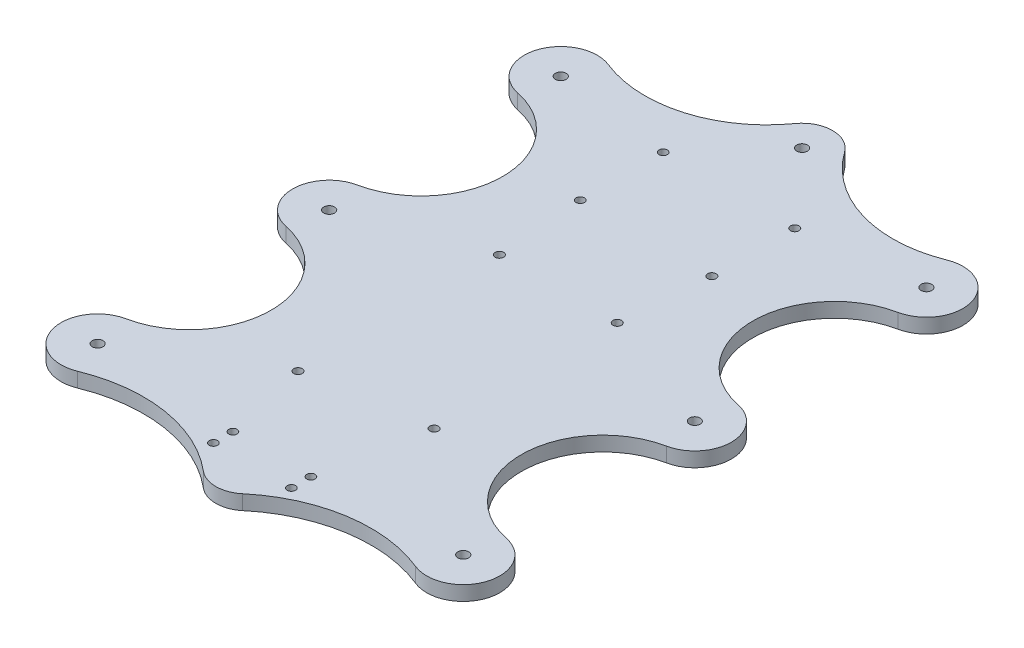
SolidWorks part; units mm, degrees
ref_plane "Front Plane" through (0, 0, 0) normal (0, 0, 1) x (1, 0, 0)
ref_plane "Top Plane" through (0, 0, 0) normal (0, 1, 0) x (1, 0, 0)
ref_plane "Right Plane" through (0, 0, 0) normal (1, 0, 0) x (0, 0, -1)
sketch "Sketch1" plane through (0, 0, 0) normal (0, 1, 0) x (1, 0, 0)
  line L0 (-75, 0) -> (75, 0) construction
  line L1 (-75, -95) -> (-75, -190) construction
  line L3 (0, 0) -> (0, -204) construction
  line L4 (0, 0) -> (0, 24)
  circle A0 centre (-75, 0) radius 15
  circle A1 centre (75, 0) radius 15
  circle A2 centre (-75, -95) radius 15
  circle A3 centre (75, -95) radius 15
  circle A4 centre (-75, -190) radius 15
  circle A5 centre (75, -190) radius 15
  circle A6 centre (-84.798, -142.5) radius 33.5
  circle A10 centre (0, -204) radius 12.5
  circle A11 centre (0, 24) radius 12.5
  circle A12 centre (-46.7001, -259.4559) radius 60
  circle A13 centre (46.7001, -259.4559) radius 60
  circle A14 centre (-50.8455, 60.3453) radius 50
  circle A15 centre (50.8455, 60.3453) radius 50
  circle A16 centre (84.798, -142.5) radius 33.5
  circle A17 centre (-84.798, -47.5) radius 33.5
  circle A18 centre (84.798, -47.5) radius 33.5
  dimension "D3" = 30
  dimension "D4" = 30
  dimension "D10" = 25
  dimension "D12" = 25
  dimension "D13" = 120
  dimension "D14" = 120
  dimension "D15" = 100
  dimension "D16" = 100
  dimension "D6" = 67
  dimension "D7" = 67
  dimension "D8" = 67
  dimension "D17" = 67
  dimension "D1" = 3
  dimension "D2" = 150
  dimension "D5" = 95
  dimension "D9" = 228
  dimension "D11" = 24
extrude "Boss-Extrude1" add sketch "Sketch1" along normal blind 6
sketch "Sketch2" plane through (0, 0, 0) normal (0, -1, 0) x (1, 0, 0)
  circle A0 centre (-75, 190) radius 2.2
  circle A1 centre (-75, 95) radius 2.2
  circle A2 centre (-75, 0) radius 2.2
  circle A3 centre (75, 0) radius 2.2
  circle A4 centre (75, 95) radius 2.2
  circle A5 centre (75, 190) radius 2.2
  dimension "D1" = 4.4
  dimension "D2" = 4.4
  dimension "D3" = 4.4
  dimension "D4" = 4.4
  dimension "D5" = 4.4
  dimension "D6" = 4.4
extrude "Cut-Extrude1" cut sketch "Sketch2" against normal through all
sketch "Sketch3" plane through (0, 6, 0) normal (0, 1, 0) x (1, 0, 0)
  line L0 (0, -216.5) -> (0, -189.6086) construction
  circle A0 centre (-16, -193.5) radius 1.7
  circle A1 centre (16, -193.5) radius 1.7
  circle A2 centre (-16, -201.5) radius 1.7
  circle A3 centre (16, -201.5) radius 1.7
  arc A4 (-8.0517, -213.5614) -> (8.0517, -213.5614) centre (0, -204) ccw construction
  point P15 (0, -216.5)
  dimension "D1" = 3.4
  dimension "D2" = 3.4
  dimension "D3" = 3.4
  dimension "D4" = 3.4
  dimension "D5" = 32
  dimension "D6" = 8
  dimension "D7" = 15
  dimension "D8" = 16
extrude "Cut-Extrude2" cut sketch "Sketch3" against normal up to next
sketch "Sketch4" plane through (0, 6, 0) normal (0, 1, 0) x (1, 0, 0)
  line L0 (-34.7155, -59.5) -> (34.7155, -59.5)
  line L5 (-38.2335, -69.5) -> (38.2335, -69.5)
  line L6 (38.2335, -120.5) -> (-38.2335, -120.5)
  line L9 (34.7155, -130.5) -> (-34.7155, -130.5)
  line L11 (-23, -185.1436) -> (-23, -1.692)
  line L12 (-15, 2.5604) -> (-15, -188.188)
  line L14 (15, -188.188) -> (15, 2.5604)
  line L16 (23, -185.1436) -> (23, -1.692)
  arc A22 (-5.0509, 10.0775) -> (5.0509, 10.0775) centre (0, 4.5333) cw
  arc A23 (37.833, -6.398) -> (42.5504, -18.0485) centre (36.3978, -13.7594) cw
  arc A24 (54.2502, -88.9619) -> (54.2502, -101.0381) centre (49.8015, -95) cw
  arc A25 (41.65, -170.6158) -> (36.3605, -182.1442) centre (35.3663, -174.7104) cw
  arc A26 (4.0965, -194.1188) -> (-4.0965, -194.1188) centre (0, -187.8364) cw
  arc A27 (-36.3605, -182.1442) -> (-41.65, -170.6158) centre (-35.3663, -174.7104) cw
  arc A28 (-54.2502, -101.0381) -> (-54.2502, -88.9619) centre (-49.8015, -95) cw
  arc A29 (-37.833, -6.398) -> (-42.5504, -18.0485) centre (-36.3978, -13.7594) ccw
  arc A38 (0, 15.193) -> (52.1859, -7.6414) centre (50.8455, 60.3453) ccw
  arc A39 (-52.1859, -7.6414) -> (0, 15.193) centre (-50.8455, 60.3453) ccw
  arc A40 (-64.8982, -95) -> (-52.1859, -7.6414) centre (-84.798, -47.5) ccw
  arc A41 (-51.2682, -181.5897) -> (-64.8982, -95) centre (-84.798, -142.5) ccw
  arc A42 (0, -196.981) -> (-51.2682, -181.5897) centre (-46.7001, -259.4559) ccw
  arc A43 (51.2682, -181.5897) -> (0, -196.981) centre (46.7001, -259.4559) ccw
  arc A44 (64.8982, -95) -> (51.2682, -181.5897) centre (84.798, -142.5) ccw
  arc A45 (52.1859, -7.6414) -> (64.8982, -95) centre (84.798, -47.5) ccw
  arc A46 (5.0509, 10.0775) -> (37.833, -6.398) centre (50.8455, 60.3453) ccw
  arc A47 (-37.833, -6.398) -> (-5.0509, 10.0775) centre (-50.8455, 60.3453) ccw
  arc A48 (-54.2502, -88.9619) -> (-42.5504, -18.0485) centre (-84.798, -47.5) ccw
  arc A49 (-41.65, -170.6158) -> (-54.2502, -101.0381) centre (-84.798, -142.5) ccw
  arc A50 (-4.0965, -194.1188) -> (-36.3605, -182.1442) centre (-46.7001, -259.4559) ccw
  arc A51 (36.3605, -182.1442) -> (4.0965, -194.1188) centre (46.7001, -259.4559) ccw
  arc A52 (54.2502, -101.0381) -> (41.65, -170.6158) centre (84.798, -142.5) ccw
  arc A53 (42.5504, -18.0485) -> (54.2502, -88.9619) centre (84.798, -47.5) ccw
  dimension "D2" = 7.5
  dimension "D3" = 10
  dimension "D4" = 12
  dimension "D5" = 10
  dimension "D6" = 12
  dimension "D7" = 8
  dimension "D8" = 8
  dimension "D9" = 15
  dimension "D10" = 15
  dimension "D1" = 18
extrude "Cut-Extrude3" [suppressed] cut sketch "Sketch4" against normal blind 10 contours A53 A23 A46 A22 A47 A29 A48 L0 | A53 L5 A48 A28 A49 L6 A52 A24 | A52 L9 A49 A27 A50 A26 A51 A25 | A48 L0 L11 A47 A29 | A53 A23 A46 L16 L0 | A53 L5 L16 L6 A52 A24 | A49 L6 L11 L5 A48 A28 | A50 L11 L9 A49 A27 | A52 L9 L16 A51 A25
sketch "Sketch5" plane through (0, 6, 0) normal (0, 1, 0) x (1, 0, 0)
  circle A0 centre (0, 24) radius 2.2
  dimension "D1" = 4.4
extrude "Cut-Extrude4" cut sketch "Sketch5" against normal up to next
sketch "Sketch6" plane through (0, 6, 0) normal (0, 1, 0) x (1, 0, 0)
  circle A0 centre (-27, -6) radius 1.7
  circle A1 centre (0, 24) radius 2.2 construction
  circle A2 centre (27, -6) radius 1.75
  circle A3 centre (-27, -40) radius 1.7
  circle A4 centre (27, -40) radius 1.75
  dimension "D1" = 3.4
  dimension "D2" = 30
  dimension "D3" = 3.5
  dimension "D4" = 54
  dimension "D5" = 27
  dimension "D6" = 2
extrude "Cut-Extrude5" cut sketch "Sketch6" against normal up to next
sketch "Sketch7" plane through (0, 6, 0) normal (0, 1, 0) x (1, 0, 0)
  circle A0 centre (-24.17, -76) radius 1.75
  circle A1 centre (24.17, -76) radius 1.75
  circle A2 centre (-24.17, -158.63) radius 1.75
  circle A3 centre (24.17, -151.13) radius 1.75
  circle A4 centre (-27, -40) radius 1.7 construction
  dimension "D1" = 3.5
  dimension "D2" = 3.5
  dimension "D3" = 3.5
  dimension "D4" = 3.5
  dimension "D8" = 36
  dimension "D5" = 48.34
  dimension "D6" = 82.63
  dimension "D7" = 75.13
  dimension "D9" = 24.17
extrude "Cut-Extrude6" cut sketch "Sketch7" against normal up to next
